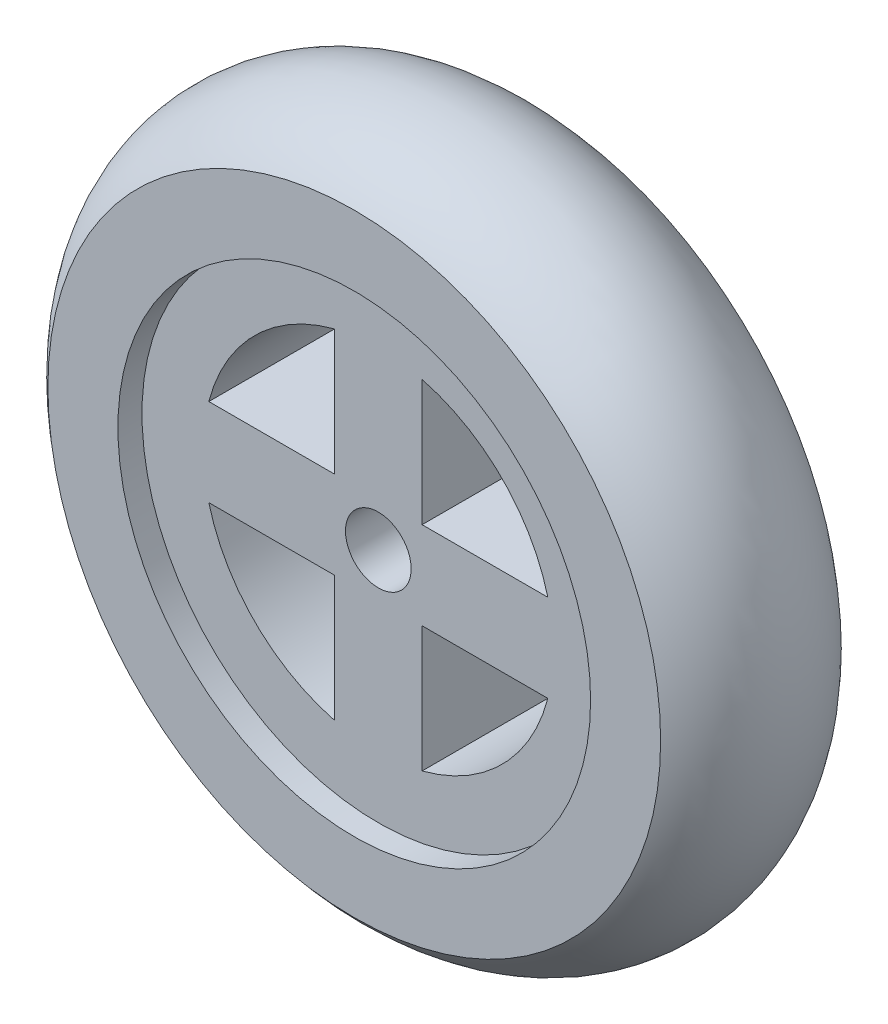
SolidWorks part; units mm, degrees
material "Rubber"
ref_plane "Front Plane" through (0, 0, 0) normal (0, 0, 1) x (1, 0, 0)
ref_plane "Top Plane" through (0, 0, 0) normal (0, 1, 0) x (1, 0, 0)
ref_plane "Right Plane" through (0, 0, 0) normal (1, 0, 0) x (0, 0, -1)
sketch "Sketch2" plane through (0, 0, 0) normal (0, 1, 0) x (1, 0, 0)
  line L0 (0, -729.4555) -> (0, 35743.3182) construction
  line L1 (54, 15) -> (54, 20.5)
  line L2 (40, -15) -> (54, -15)
  line L3 (40, -15) -> (40, 15)
  line L4 (40, 15) -> (54, 15)
  line L6 (54, 20.5) -> (70, 20.5)
  line L8 (54, -15) -> (54, -20.5)
  line L9 (54, -20.5) -> (70, -20.5)
  arc A0 (70, 20.5) -> (70, -20.5) centre (54.0078, 0) cw
  point P7 (40, 0)
  dimension "D5" = 26
  dimension "D1" = 40
  dimension "D2" = 14
  dimension "D3" = 5.5
  dimension "D4" = 16
  dimension "D6" = 30
revolve "Revolve1" add sketch "Sketch2" angle 360 about L0
sketch "Sketch3" plane through (0, 0, 0) normal (0, 1, 0) x (1, 0, 0)
  line L0 (-40, 15) -> (40, 15)
  line L1 (40, 15) -> (40, -15)
  line L2 (40, -15) -> (40, 15) construction
  line L3 (40, -15) -> (-40, -15)
  line L4 (-40, -15) -> (40, -15) construction
  line L5 (-54, -15) -> (54, -15) construction
  line L6 (-40, -15) -> (-40, 15)
  line L7 (0, -1000) -> (0, 49000) construction
extrude "Boss-Extrude1" add sketch "Sketch3" along normal mid plane 20
ref_plane "Plane1" through (0, 0, 0) normal (-0.7071, 0.7071, 0) x (0, 0, -1)
mirror "Mirror1" about plane through (0, 0, 0) normal (-0.7071, 0.7071, 0) of "Boss-Extrude1"
sketch "Sketch5" plane through (0, 0, -15) normal (0, 0, -1) x (-1, 0, 0)
  circle A0 centre (0, 0) radius 7.5
  dimension "D1" = 15
extrude "Cut-Extrude1" cut sketch "Sketch5" against normal through all both and the other way through all
